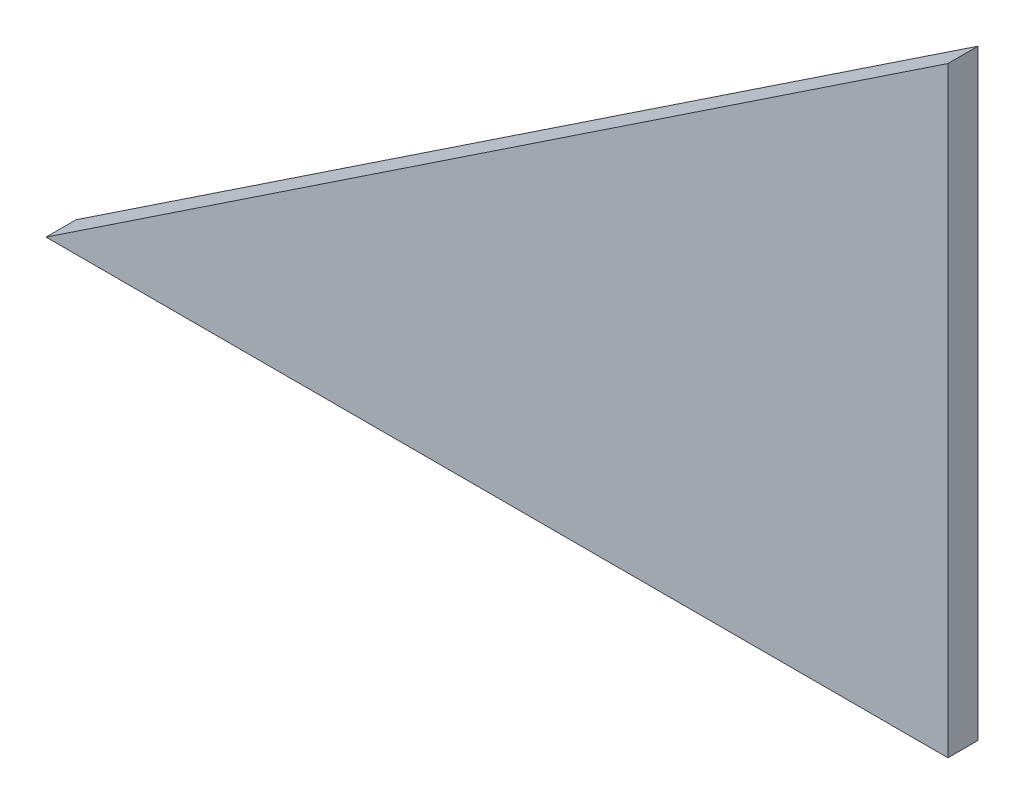
SolidWorks part; units mm, degrees
material "1060 Alloy"
ref_plane "Front Plane" through (0, 0, 0) normal (0, 0, 1) x (1, 0, 0)
ref_plane "Top Plane" through (0, 0, 0) normal (0, 1, 0) x (1, 0, 0)
ref_plane "Right Plane" through (0, 0, 0) normal (1, 0, 0) x (0, 0, -1)
sketch "Sketch1" plane through (0, 0, 23.6765) normal (0, 0, -1) x (-1, 0, 0)
  line L0 (-235.0366, 11.9601) -> (-235.0366, 37.3601)
  line L1 (-235.0366, 11.9601) -> (-6.3096, 11.9601) construction
  line L2 (-235.0366, 13.2301) -> (-235.0366, 54.5051) construction
  line L3 (-235.0366, 37.3601) -> (-196.9366, 11.9601)
  line L4 (-196.9366, 11.9601) -> (-235.0366, 11.9601)
  dimension "D1" = 25.4
  dimension "D2" = 38.1
extrude "Boss-Extrude1" add sketch "Sketch1" along normal blind 1.27
